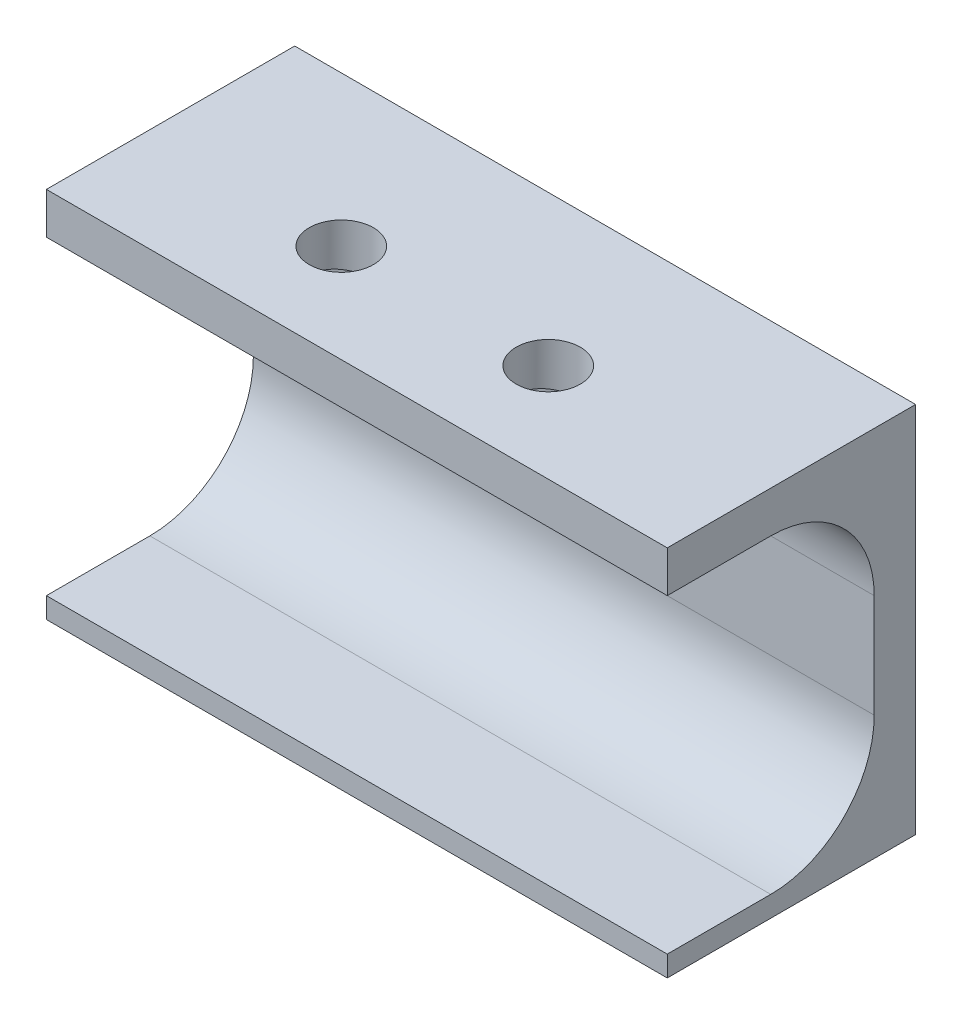
SolidWorks part; units mm, degrees
ref_plane "Front Plane" through (0, 0, 0) normal (0, 0, 1) x (1, 0, 0)
ref_plane "Top Plane" through (0, 0, 0) normal (0, 1, 0) x (1, 0, 0)
ref_plane "Right Plane" through (0, 0, 0) normal (1, 0, 0) x (0, 0, -1)
sketch "Sketch1" plane through (0, 0, 0) normal (1, 0, 0) x (0, 0, -1)
  line L0 (-6.5391, 14.6096) -> (-11.5391, 14.6096)
  line L1 (-11.5391, -1.3904) -> (0.4609, -1.3904)
  line L2 (-11.5391, -1.3904) -> (-11.5391, -0.3904)
  line L3 (-11.5391, 16.6096) -> (0.4609, 16.6096)
  line L4 (0.4609, -1.3904) -> (0.4609, 16.6096)
  line L7 (-6.5391, -0.3904) -> (-8.5391, -0.3904)
  line L8 (-1.5391, 4.6096) -> (-1.5391, 9.6096)
  line L11 (-8.5391, -0.3904) -> (-11.5391, -0.3904)
  line L12 (-11.5391, 14.6096) -> (-11.5391, 16.6096)
  arc A2 (-6.5391, -0.3904) -> (-1.5391, 4.6096) centre (-6.5391, 4.6096) ccw
  arc A5 (-1.5391, 9.6096) -> (-6.5391, 14.6096) centre (-6.5391, 9.6096) ccw
  point P6 (-10.2458, 6.3708)
  point P13 (-13.5391, 14.6096)
  point P18 (-1.5391, 14.6096)
  dimension "D4" = 2
  dimension "D7" = 5
  dimension "D1" = 18
  dimension "D2" = 12
  dimension "D3" = 1
  dimension "D6" = 12
extrude "Boss-Extrude1" add sketch "Sketch1" along normal blind 30
sketch "Sketch2" plane through (0, 16.6096, 0) normal (0, 1, 0) x (1, 0, 0)
  line L0 (30, 0.4609) -> (30, -11.5391) construction
  line L2 (30, -11.5391) -> (0, -11.5391) construction
  circle A0 centre (-10.5, -6.7891) radius 1.55
  circle A1 centre (-20.5, -6.7891) radius 1.55
  circle A2 centre (9.5, -6.7891) radius 1.55
  circle A3 centre (19.5, -6.7891) radius 1.55
  dimension "D1" = 3.1
  dimension "D2" = 10
  dimension "D3" = 10
  dimension "D4" = 20
  dimension "D5" = 10.5
  dimension "D6" = 4.75
  dimension "D7" = 4.75
  dimension "D8" = 4.75
  dimension "D9" = 4.75
extrude "Cut-Extrude1" cut sketch "Sketch2" against normal blind 5
